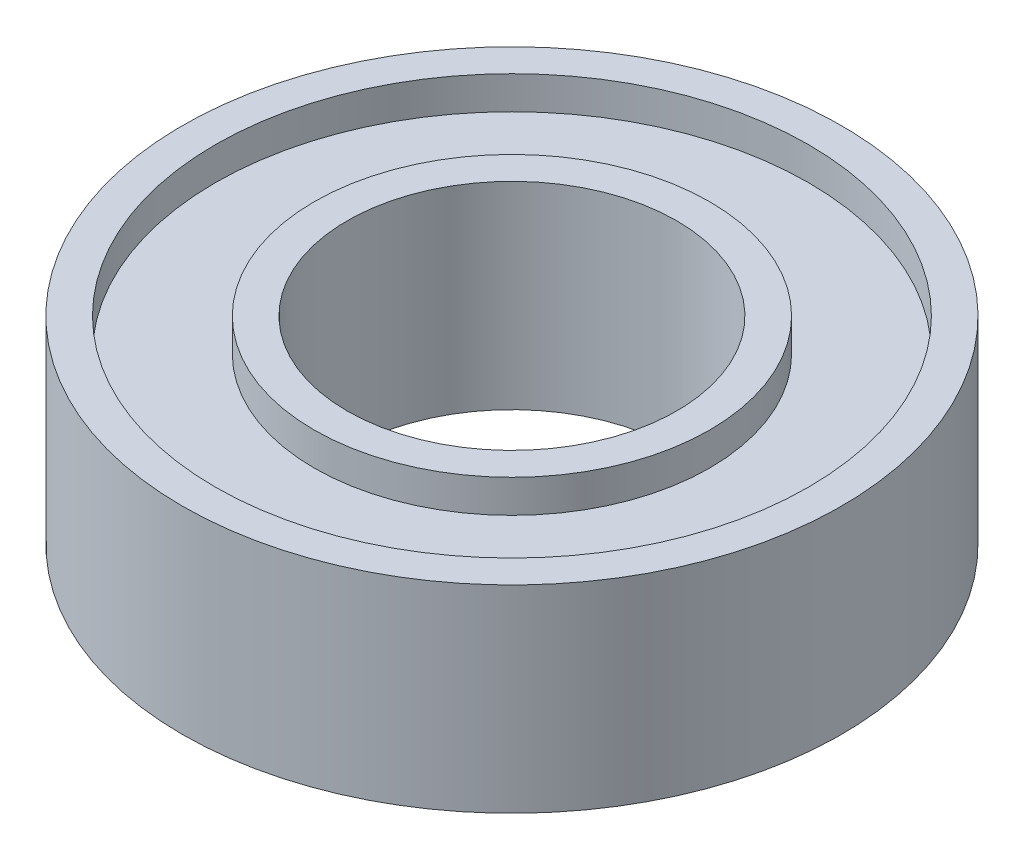
SolidWorks part; units mm, degrees
material "Chrome Stainless Steel"
ref_plane "Front Plane" through (0, 0, 0) normal (0, 0, 1) x (1, 0, 0)
ref_plane "Top Plane" through (0, 0, 0) normal (0, 1, 0) x (1, 0, 0)
ref_plane "Right Plane" through (0, 0, 0) normal (1, 0, 0) x (0, 0, -1)
sketch "Sketch1" plane through (0, 0, 0) normal (0, 1, 0) x (1, 0, 0)
  circle A0 centre (0, 0) radius 10
  dimension "D1" = 20
extrude "main extrusion" add sketch "Sketch1" along normal blind 6 contours A0
sketch "Sketch2" plane through (0, 6, 0) normal (0, 1, 0) x (1, 0, 0)
  circle A0 centre (0, 0) radius 5
  dimension "D1" = 10
extrude "ID bore" cut sketch "Sketch2" against normal blind 20
sketch "Sketch3" plane through (0, 6, 0) normal (0, 1, 0) x (1, 0, 0)
  circle A0 centre (0, 0) radius 9
  circle A1 centre (0, 0) radius 6
  dimension "D1" = 12
  dimension "D2" = 18
extrude "seal recess" cut sketch "Sketch3" against normal blind 1
equation "\"D1@Sketch1\"=\"bearing OD\""
equation "\"D1@main extrusion\" = \"bearing depth\""
equation "\"D1@Sketch2\"=\"bearing ID\""
equation "\"bearing OD\" = 20mm"
equation "\"bearing outer race thickness\"= 1mm"
equation "\"bearing ID\"= 10mm"
equation "\"bearing depth\"= 6mm"
equation "\"bearing inner race thickness\"= 1mm"
equation "\"seal OD\" = 20mm"
equation "\"seal ID\"= 8mm"
equation "\"seal depth\"= 6mm"
equation "\"motor to housing distance\"= 60mm"
equation "\"motor mount pattern diameter\"= 30mm"
equation "\"motor mount coupler shaft hole diameter\"= \"coupler shaft base diameter\"+ 4mm"
equation "\"motor mount to housing m8 screw hole diameter\"= 8.5mm"
equation "\"motor mount to housing m8 screw post radius\"= ( 3 * \"motor mount to housing m8 screw hole diameter\" ) / 2"
equation "\"motor mount to housing m8 pattern diameter\"= 100mm"
equation "\"motor mount to housing m4 screw hole diamater\"= 4mm"
equation "\"motor mount to housing m4 head diameter\"= 7.25mm"
equation "\"motor mount to housing m4 head depth\"= 4mm"
equation "\"motor mount plate thickness\"= 6mm + \"motor mount to housing m4 head depth\""
equation "\"motor mount m6 screw hole diameter\"= 6.5mm"
equation "\"motor mount m6 screw socket head diameter\"= 10.5mm"
equation "\"motor mount m6 screw socket head depth\"= 6mm"
equation "\"motor shaft pride\"= 32mm"
equation "\"motor shaft flat section length from tip\"= 25.7mm"
equation "\"motor shaft bore end clearance\"= 2mm"
equation "\"motor mount shaft hole depth\"= \"motor shaft pride\""
equation "\"coupler shaft set screw drill hole diameter\"= 6mm"
equation "\"coupler shaft motor shaft hole diameter\"= 8mm"
equation "\"coupler shaft base diameter\"= 18mm"
equation "\"coupler shaft base length\"= \"motor mount shaft hole depth\" + 10mm"
equation "\"coupler shaft second section diameter\"= \"bearing ID\" + \"bearing inner race thickness\" * 2"
equation "\"coupler shaft third section diamater\"= \"bearing ID\""
equation "\"coupler shaft second section length\"= \"motor to housing distance\" -  \"coupler shaft base length\" - 2mm"
equation "\"coupler shaft set screw 1 distance\"= \"motor mount shaft hole depth\" / 3"
equation "\"coupler shaft set screw 2 distance\"= \"motor mount shaft hole depth\" * 4 / 5"
equation "\"housing bearing seat lip thickness\" = 2mm"
equation "\"housing base thickness\"= \"housing bearing seat lip thickness\" + \"seal depth\" + \"bearing depth\""
equation "\"impeller base outer diameter\"= 1.75in"
equation "\"impeller base outer thickness\"= 1mm"
equation "\"impeller base center thickness\"= 5mm"
equation "\"impeller number of vanes\"= 8"
equation "\"impeller vane outer height`\"= 4mm"
equation "\"impeller vane inner height\"= 8mm"
equation "\"impeller primary vane opening diamater\"= 10mm"
equation "\"impeller shaft bore size\"=4mm "
equation "\"impeller vane inner thickness\"= .75mm"
equation "\"impeller vane outer thickness\"= 1.5mm"
equation "\"impeller primary vane entrance angle\"= 20deg"
equation "\"impeller secondary vane entrance angle\"= 20deg"
equation "\"impeller secondary vane opening diameter\"= 10mm"
equation "\"housing top impeller vertical clearance\"= .5mm"
equation "\"housing top impeller horizontal clearance\"= .5mm"
equation "\"housing top impeller bottom clearance\"= 1mm"
equation "\"housing top impeller cavity height\"= \"housing top impeller bottom clearance\" + \"impeller base center thickness\" + \"impeller vane inner height\" + \"housing top impeller vertical clearance\""
equation "\"housing top impeller cavity diameter\"= 2 * \"housing top impeller horizontal clearance\" + \"impeller base outer diameter\""
equation "\"housing top impeller cavity tip height\"= \"housing top impeller bottom clearance\" + \"housing top impeller vertical clearance\" + \"impeller base outer thickness\" + \"impeller vane outer height\""
equation "\"housing top entrance OD\"= 20mm"
equation "\"housing top exit OD\"= 5mm"
equation "\"housing top o-ring channel height\"= 1.5mm"
equation "\"housing top o ring channel width\"= 1.5mm"
equation "\"housing top threaded inlet depth\"= 8mm"
equation "\"housing top total thickness\"= \"housing top threaded inlet depth\" + \"housing top impeller cavity height\""
equation "\"housing top total width\"= 10mm"
equation "\"housing top exit threaded diameter\"= 8mm"
equation "\"housing top exit threaded depth\"= 8mm"
equation "\"D2@Sketch3\"=\"bearing OD\"-\"bearing outer race thickness\"*2"
equation "\"D1@Sketch3\"=\"bearing ID\"+\"bearing inner race thickness\"*2"
